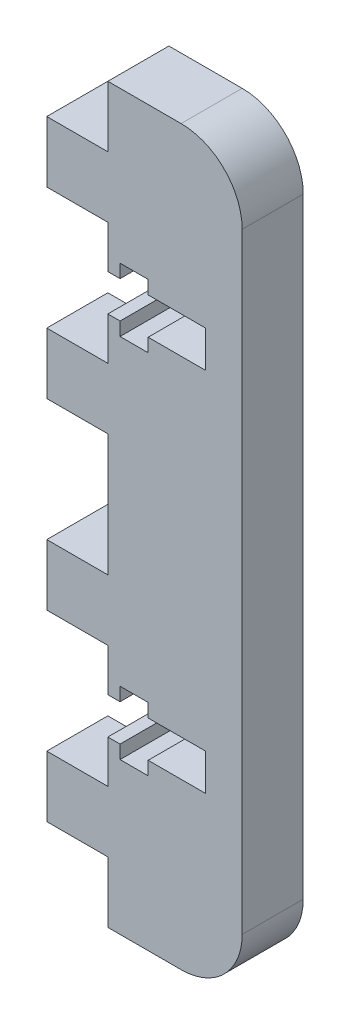
SolidWorks part; units mm, degrees
ref_plane "Front Plane" through (0, 0, 0) normal (0, 0, 1) x (1, 0, 0)
ref_plane "Top Plane" through (0, 0, 0) normal (0, 1, 0) x (1, 0, 0)
ref_plane "Right Plane" through (0, 0, 0) normal (1, 0, 0) x (0, 0, -1)
sketch "Sketch1" plane through (0, 0, 0) normal (0, 0, 1) x (1, 0, 0)
  line L0 (0, 60) -> (0, 55)
  line L1 (0, 0) -> (11, 0)
  line L2 (0, 0) -> (0, 60) construction
  line L3 (0, 60) -> (11, 60)
  line L4 (11, 0) -> (11, 60)
  line L5 (0, 35) -> (0, 25)
  line L6 (0, 5) -> (0, 0)
  line L7 (0, 45) -> (11.2208, 45) construction
  line L8 (0, 46.5) -> (0, 50)
  line L9 (-5, 50) -> (-5, 55)
  line L10 (-5, 55) -> (0, 55)
  line L11 (-5, 50) -> (0, 50)
  line L12 (0, 43.5) -> (0, 40)
  line L13 (0, 40) -> (-5, 40)
  line L14 (-5, 40) -> (-5, 35)
  line L15 (-5, 35) -> (0, 35)
  line L16 (0, 15) -> (11.2208, 15) construction
  line L17 (0, 16.5) -> (0, 20)
  line L18 (-5, 20) -> (-5, 25)
  line L19 (-5, 25) -> (0, 25)
  line L20 (-5, 20) -> (0, 20)
  line L21 (0, 13.5) -> (0, 10)
  line L22 (0, 10) -> (-5, 10)
  line L23 (-5, 10) -> (-5, 5)
  line L24 (-5, 5) -> (0, 5)
  line L25 (0, 46.5) -> (0, 43.5) construction
  line L26 (0, 43.5) -> (1, 43.5)
  line L27 (3.3, 43.5) -> (3.3, 42.4)
  line L28 (1, 47.6) -> (3.3, 47.6)
  line L29 (1, 42.4) -> (1, 43.5)
  line L30 (3.3, 43.5) -> (8, 43.5)
  line L31 (8, 43.5) -> (8, 46.5)
  line L32 (8, 46.5) -> (3.3, 46.5)
  line L33 (1, 46.5) -> (1, 47.6)
  line L34 (3.3, 42.4) -> (1, 42.4)
  line L35 (3.3, 47.6) -> (3.3, 46.5)
  line L36 (1, 46.5) -> (0, 46.5)
  line L37 (8, 45) -> (0, 45) construction
  line L38 (0, 16.5) -> (0, 13.5) construction
  line L39 (0, 13.5) -> (1, 13.5)
  line L40 (3.3, 13.5) -> (3.3, 12.4)
  line L41 (1, 17.6) -> (3.3, 17.6)
  line L42 (1, 12.4) -> (1, 13.5)
  line L43 (3.3, 13.5) -> (8, 13.5)
  line L44 (8, 13.5) -> (8, 16.5)
  line L45 (8, 16.5) -> (3.3, 16.5)
  line L46 (1, 16.5) -> (1, 17.6)
  line L47 (3.3, 12.4) -> (1, 12.4)
  line L48 (3.3, 17.6) -> (3.3, 16.5)
  line L49 (1, 16.5) -> (0, 16.5)
  line L50 (8, 15) -> (0, 15) construction
  point P11 (-2.5, 25)
  point P12 (-2.5, 5)
  dimension "D1" = 10
  dimension "D2" = 5
  dimension "D3" = 5
  dimension "D4" = 10
  dimension "16.8" = 11
  dimension "D5" = 5
  dimension "D6" = 5
  dimension "D7" = 10
  dimension "D8" = 5
  dimension "D9" = 5
  dimension "D10" = 5.2
  dimension "D11" = 3
  dimension "D12" = 2.3
  dimension "D13" = 1
  dimension "D14" = 8
  dimension "D15" = 5.2
  dimension "D16" = 3
  dimension "D17" = 2.3
  dimension "D18" = 1
  dimension "D19" = 8
extrude "Boss-Extrude1" add sketch "Sketch1" along normal blind 5
fillet "Fillet1" radius 5 2 edges at (11, 0, 2.5) (11, 60, 2.5)
